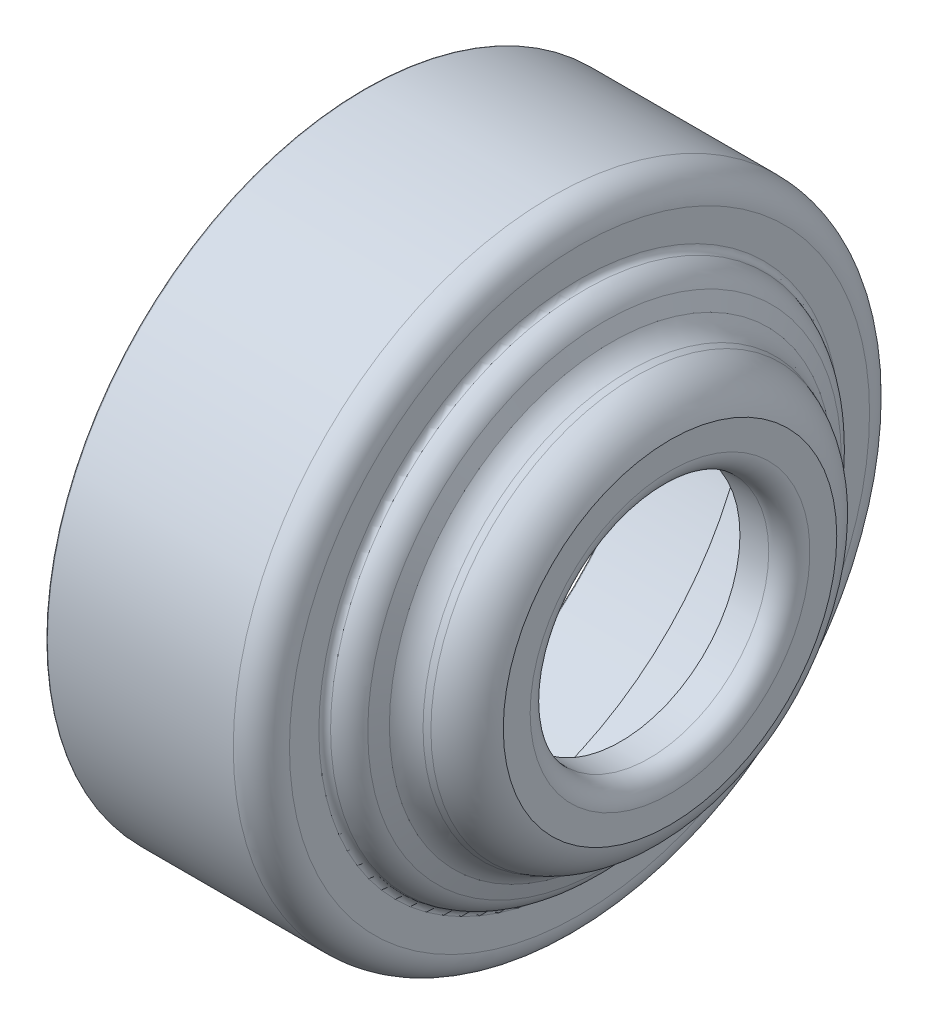
SolidWorks part; units mm, degrees
ref_plane "前视基准面" through (0, 0, 0) normal (0, 0, 1) x (1, 0, 0)
ref_plane "上视基准面" through (0, 0, 0) normal (0, 1, 0) x (1, 0, 0)
ref_plane "右视基准面" through (0, 0, 0) normal (1, 0, 0) x (0, 0, -1)
sketch "草图1" plane through (0, 0, 0) normal (0, 0, 1) x (1, 0, 0)
  line L0 (-28.9725, 0) -> (27.6414, 0) construction
  line L1 (0, 33.7643) -> (0, -22.2949) construction
  line L9 (-14.9, 22) -> (-7.9, 22)
  line L10 (-0.4, 20.9) -> (-0.4, 17.7)
  line L11 (-0.1, 17.4) -> (0.6, 17.4)
  line L12 (1.5207, 16.7949) -> (2.0219, 15.6141)
  line L13 (4.0243, 13.9299) -> (4.4661, 13.7651)
  line L14 (6.2, 12) -> (6.2, 9.9)
  line L15 (5.7, 9.4) -> (3.8, 9.4)
  line L17 (3.8, 9.4) -> (3.8, 8.7)
  line L18 (-14.9, 23.2) -> (-1.25, 23.2)
  line L19 (-0.4, 23.7801) -> (-0.4, -6.5039) construction
  line L20 (0.8, 21.15) -> (0.8, 19.0082)
  line L21 (-14.9, 23.2) -> (-14.9, 22)
  line L22 (2.6244, 17.2658) -> (3.0938, 16.1601)
  line L23 (4.4435, 15.0542) -> (4.8612, 14.8985)
  line L24 (7.4, 12.1596) -> (7.4, 10.2)
  line L26 (6.2, 12) -> (6.2, 10.9875) construction
  line L27 (0.8, 21.15) -> (0.8, 18.5911) construction
  line L28 (0.8, 18.5911) -> (0.8, 18.5911) construction
  line L29 (3.8, 9.4) -> (3.8, 9) construction
  line L30 (5.5608, 8.2) -> (4.6944, 8.2) construction
  line L31 (5.6477, 9.4) -> (3.8, 9.4) construction
  line L32 (4.6944, 8.2) -> (4.6944, 8.2) construction
  line L33 (7.4, 12.1596) -> (7.4, 11.5217) construction
  line L34 (-7.9, 22) -> (-7.9, 21.4)
  line L35 (-7.9, 21.4) -> (-0.9, 21.4)
  line L36 (-0.4, 21.15) -> (-0.4, 17.7) construction
  line L37 (3.8, 8.7) -> (5.9, 8.7)
  line L38 (-14.9, 22) -> (-1.25, 22) construction
  arc A8 (1.5207, 16.7949) -> (0.6, 17.4) centre (0.602, 16.4) ccw
  arc A9 (2.0219, 15.6141) -> (4.0243, 13.9299) centre (5.3857, 17.5808) ccw
  arc A10 (6.2, 12) -> (4.4661, 13.7651) centre (3.6572, 11.2364) ccw
  arc A12 (-0.1, 17.4) -> (-0.4, 17.7) centre (-0.1, 17.7) cw
  arc A13 (0.8, 21.15) -> (-1.25, 23.2) centre (-1.25, 21.15) ccw
  arc A14 (7.4, 11.5217) -> (5.5608, 8.2) centre (5.8037, 10.2356) cw construction
  arc A15 (2.6244, 17.2658) -> (1.1707, 18.5252) centre (0.602, 16.4) ccw
  arc A16 (3.0938, 16.1601) -> (4.4435, 15.0542) centre (5.3857, 17.5808) ccw
  arc A17 (7.4, 12.1596) -> (4.8612, 14.8985) centre (3.6572, 11.2364) ccw
  arc A19 (2.6244, 17.2658) -> (0.8, 18.5911) centre (0.602, 16.4) ccw construction
  arc A20 (0.8, 19.0082) -> (1.1707, 18.5252) centre (1.3, 19.0082) ccw
  arc A21 (0.8, 18.5911) -> (0.8, 18.5911) centre (0.8, 18.5911) cw construction
  arc A22 (6.2, 10.9875) -> (5.6477, 9.4) centre (5.8037, 10.2356) cw construction
  arc A23 (6.2, 9.9) -> (5.7, 9.4) centre (5.7, 9.9) cw
  arc A25 (-0.4, 21.15) -> (-1.25, 22) centre (-1.25, 21.15) ccw construction
  arc A26 (-0.4, 20.9) -> (-0.9, 21.4) centre (-0.9, 20.9) ccw
  arc A27 (5.9, 8.7) -> (7.4, 10.2) centre (5.9, 10.2) ccw
  point P15 (0, 22.4)
  point P24 (3, 14.5)
  point P27 (7, 13)
  point P30 (7, 9)
  point P66 (-7.9, 21.7)
  point P69 (7.4, 11.1798)
  dimension "D11" = 1.8
  dimension "D12" = 0.4
  dimension "D13" = 0.5
  dimension "D14" = 2.4
  dimension "D15" = 1.5
  dimension "D16" = 7.5
  dimension "D5" = 0.3
  dimension "D8" = 0.5
  dimension "D19" = 0.5
  dimension "D20" = 2.05
  dimension "D23" = 1
  dimension "D24" = 2.2
  dimension "D2" = 18.8
  dimension "D3" = 34.8
  dimension "D4" = 29
  dimension "D6" = 1.2
  dimension "D7" = 3
  dimension "D9" = 24
  dimension "D10" = 3.8
  dimension "D18" = 44
  dimension "D17" = 7
  dimension "D21" = 1.2
  dimension "D22" = 1.2
  dimension "D25" = 0.7
  dimension "D26" = 1
  dimension "D27" = 23
  dimension "D28" = 14.1
revolve "旋转1" add sketch "草图1" angle 360 about L0
fillet "圆角2" radius 0.1 2 edges at (-14.9, 0, 22) (-14.9, 0, 23.2)
